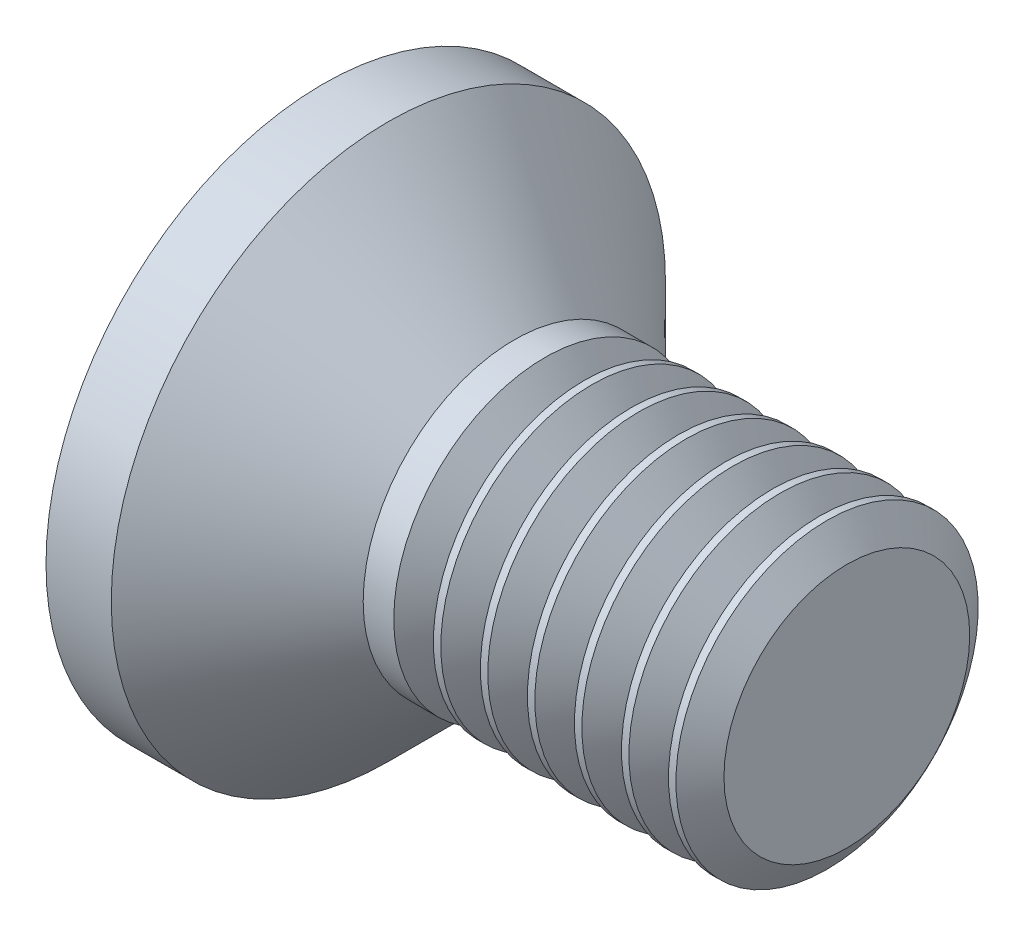
SolidWorks part; units mm, degrees
revolve "Base-Revolve" add sketch "BodySke" angle 360 about L4
sketch "BodySke" plane through (0, 0, 0) normal (0, 0, 1) x (1, 0, 0)
  line L0 (0, 0) -> (5.7277, 0)
  line L1 (5.7277, 0) -> (5.7277, 1.5)
  line L2 (5.7277, 1.5) -> (2.4277, 1.5)
  line L3 (2.4277, 1.5) -> (-7.1953, 11.123) construction
  line L4 (-15.875, 0) -> (82.55, 0) construction
  line L5 (2.4277, -1.5) -> (-7.1953, -11.123) construction
  line L6 (2.9277, 4.675) -> (2.9277, -11.2) construction
  line L7 (0.7277, 8.7375) -> (0.7277, -7.1375) construction
  line L8 (2.4277, 1.5) -> (1.1777, 2.75)
  line L9 (1.1777, 2.75) -> (0.53, 2.75)
  arc A0 (0, 0) -> (0.53, 2.75) centre (7.4, 0) cw
  arc A1 (0.7277, 3.2) -> (0, 0) centre (7.4, 0) ccw construction
  dimension "Crown_rad" = 7.4
  dimension "Diameter" = 3
  dimension "Advance" = 0.5
  dimension "Thread_nom" = 5
  dimension "Head_ang" = 90
  dimension "D3" = 6.4
  dimension "Side_ht" = 1.7
  dimension "D4" = 0.7277
  dimension "Length" = 5
  dimension "Head_dia" = 5.5
cosmetic thread "ThreadCosmetic" [suppressed] parameters "Thread_length"=2.8, "Thread_minor"=2.439
ref_plane "Plane1" through (0, 0, 0) normal (0, 0, 1) x (1, 0, 0)
ref_plane "Plane2" through (0, 0, 0) normal (0, 1, 0) x (1, 0, 0)
ref_plane "Plane3" through (0, 0, 0) normal (1, 0, 0) x (0, 0, -1)
sketch "Sketch2" plane through (0, 0, 0) normal (1, 0, 0) x (0, 0, -1)
  line L0 (2.75, -0.5) -> (-2.75, -0.5)
  line L1 (2.75, -0.5) -> (2.75, 0.5)
  line L2 (-2.75, 0.5) -> (2.75, 0.5)
  line L3 (-2.75, 0.5) -> (-2.75, -0.5)
  dimension "D1" = 5.5
  dimension "Slot_width" = 1
  dimension "D3" = 2.75
  dimension "D4" = 0.5
extrude "Slot" [suppressed] cut sketch "Sketch2" along normal blind 1.5
sketch "Sketch3" plane through (0, 0, 0) normal (1, 0, 0) x (0, 0, -1)
  line L0 (0.415, -1.72) -> (-0.415, -1.72)
  line L1 (0.415, -1.72) -> (0.415, 1.72)
  line L2 (-0.415, 1.72) -> (0.415, 1.72)
  line L3 (-0.415, 1.72) -> (-0.415, -1.72)
  dimension "Cross_width" = 0.83
  dimension "D1" = 0.415
  dimension "Cross_dia" = 3.44
  dimension "D2" = 1.72
ref_plane "Plane4" through (2.33, 0, 0) normal (1, 0, 0) x (0, 0, -1)
sketch "Sketch4" plane through (2.33, 0, 0) normal (1, 0, 0) x (0, 0, -1)
  line L0 (0.2075, -0.2075) -> (-0.2075, -0.2075)
  line L1 (0.2075, -0.2075) -> (0.2075, 0.2075)
  line L2 (-0.2075, 0.2075) -> (0.2075, 0.2075)
  line L3 (-0.2075, 0.2075) -> (-0.2075, -0.2075)
  dimension "D1" = 0.415
  dimension "D2" = 0.415
  dimension "D3" = 0.2075
  dimension "D4" = 0.2075
loft "Cross" cut profiles "Sketch3", "Sketch4"
pattern_circular "CirPattern1" count 2 every 90 about axis through (0, 0, 0) along (1, 0, 0) of "Cross"
sketch "ThdSchSke" plane through (0, 0, 0) normal (0, 0, 1) x (1, 0, 0)
  line L0 (2.9277, -1.2195) -> (2.7313, -1.5)
  line L1 (2.9277, -1.2195) -> (3.1241, -1.5)
  line L2 (3.1241, -1.5) -> (3.1241, -1.875)
  line L3 (-3.175, 0) -> (5.1513, 0) construction
  line L5 (3.1241, -1.875) -> (2.7313, -1.875)
  line L6 (2.7313, -1.875) -> (2.7313, -1.5)
  line L8 (5.7277, -1.5) -> (5.7277, 1.5) construction
  dimension "Diameter" = 3
  dimension "Thread_minor" = 2.439
  dimension "Start" = 2.8
revolve "ThreadSchematic" cut sketch "ThdSchSke" angle 360 about L3
pattern_linear "ThdSchPat" count 7 spacing 0.4667 along (1, 0, 0) of "ThreadSchematic"
equation "\"D1@Sketch2\" = \"Head_dia@BodySke\""
equation "\"D3@Sketch2\" = \"D1@Sketch2\" / 2"
equation "\"D4@Sketch2\" = \"Slot_width@Sketch2\" / 2"
equation "\"D1@Sketch3\" = \"Cross_width@Sketch3\" / 2"
equation "\"D2@Sketch3\" = \"Cross_dia@Sketch3\" / 2"
equation "\"D1@Sketch4\" = \"Cross_width@Sketch3\"*.5"
equation "\"D2@Sketch4\" = \"D1@Sketch4\""
equation "\"D3@Sketch4\" = \"D1@Sketch4\" / 2"
equation "\"D4@Sketch4\" = \"D2@Sketch4\" / 2"
equation "\"Thread_length@ThreadCosmetic\" = ((sgn( (\"Length@BodySke\" - \"Advance@BodySke\" - \"Side_ht@BodySke\" ) - \"Thread_nom@BodySke\" )-1)*( (\"Length@BodySke\" - \"Advance@BodySke\" - \"Side_ht@BodySke\" ) - \"Thread_nom@BodySke\" ))/-2+ \"Thread_nom@BodySke\""
equation "\"Thread_minor@ThdSchSke\" = \"Thread_minor@ThreadCosmetic\""
equation "\"Diameter@ThdSchSke\" = \"Diameter@BodySke\""
equation "\"Overcut@ThdSchSke\" = \"Diameter@BodySke\" * 1.25"
equation "\"Start@ThdSchSke\" =  \"Thread_length@ThreadCosmetic\""
equation "\"Num_threads@ThdSchPat\" = int( \"Thread_length@ThreadCosmetic\" / \"Advance@BodySke\" + 0.999 )  + 1"
equation "\"Advance@ThdSchPat\" = \"Thread_length@ThreadCosmetic\" /  (\"Num_threads@ThdSchPat\" - 1) 'relax it"
